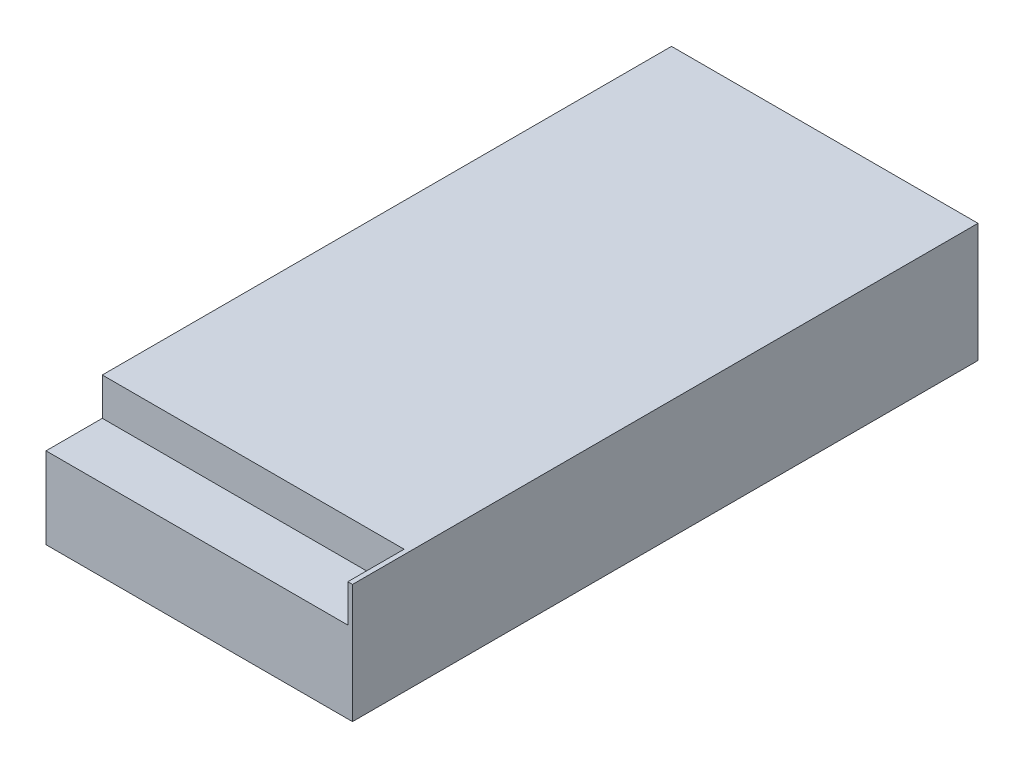
SolidWorks part; units mm, degrees
ref_plane "前视基准面" through (0, 0, 0) normal (0, 0, 1) x (1, 0, 0)
ref_plane "上视基准面" through (0, 0, 0) normal (0, 1, 0) x (1, 0, 0)
ref_plane "右视基准面" through (0, 0, 0) normal (1, 0, 0) x (0, 0, -1)
sketch "草图1" plane through (0, 0, 0) normal (0, 1, 0) x (1, 0, 0)
  line L1 (-49, 100) -> (49, 100)
  line L2 (-49, 100) -> (-49, -100)
  line L3 (-49, -100) -> (49, -100)
  line L4 (49, 100) -> (49, -100)
  line L5 (-49, 100) -> (49, -100) construction
  line L6 (-49, -100) -> (49, 100) construction
  point P0 (0, 0)
  dimension "D1" = 98
  dimension "D2" = 200
extrude "主体" add sketch "草图1" along normal blind 38
sketch "草图2" plane through (0, 38, 0) normal (0, 1, 0) x (1, 0, 0)
  line L1 (-49, -100) -> (47.5, -100)
  line L2 (-49, -100) -> (-49, -82)
  line L3 (-49, -82) -> (47.5, -82)
  line L4 (47.5, -100) -> (47.5, -82)
  line L5 (49, -100) -> (49, 100) construction
  point P7 (0, 0)
  dimension "D1" = 18
  dimension "D2" = 1.5
extrude "切除-拉伸1" cut sketch "草图2" against normal blind 12
sketch "草图3" plane through (0, 0, 0) normal (0, -1, 0) x (1, 0, 0)
  line L0 (-49, 100) -> (49, 100) construction
  line L1 (-38, 39) -> (41, 39) construction
  line L2 (-38, 39) -> (-38, -81) construction
  line L3 (-38, -81) -> (41, -81) construction
  line L4 (41, 39) -> (41, -81) construction
  line L5 (49, 100) -> (49, -100) construction
  dimension "D1" = 61
  dimension "D2" = 120
  dimension "D3" = 8
  dimension "D4" = 79
hole_wizard "M3 螺纹孔的螺纹孔钻头1" positions "草图4" profile "草图5" hole size "M3" standard "ISO"
sketch "草图4" plane through (0, 0, 0) normal (0, -1, 0) x (-1, 0, 0)
  point P0 (38, -39)
  point P3 (-41, -39)
  point P6 (38, 81)
  point P9 (-41, 81)
sketch "草图5" plane through (-38, 0, 39) normal (1, 0, 0) x (0, 0, -1)
  line L0 (0, 0) -> (0, 5.7511)
  line L1 (0, 5.7511) -> (1.25, 5)
  line L2 (1.25, 5) -> (1.25, 0)
  line L5 (1.25, 0) -> (0, 0)
  line L10 (0, 5.7511) -> (-1.25, 5) construction
  line L11 (0, -6.35) -> (0, 107.95) construction
  dimension "孔直径" = 2.5
  dimension "孔深度" = 5
  dimension "导头角度" = 118
